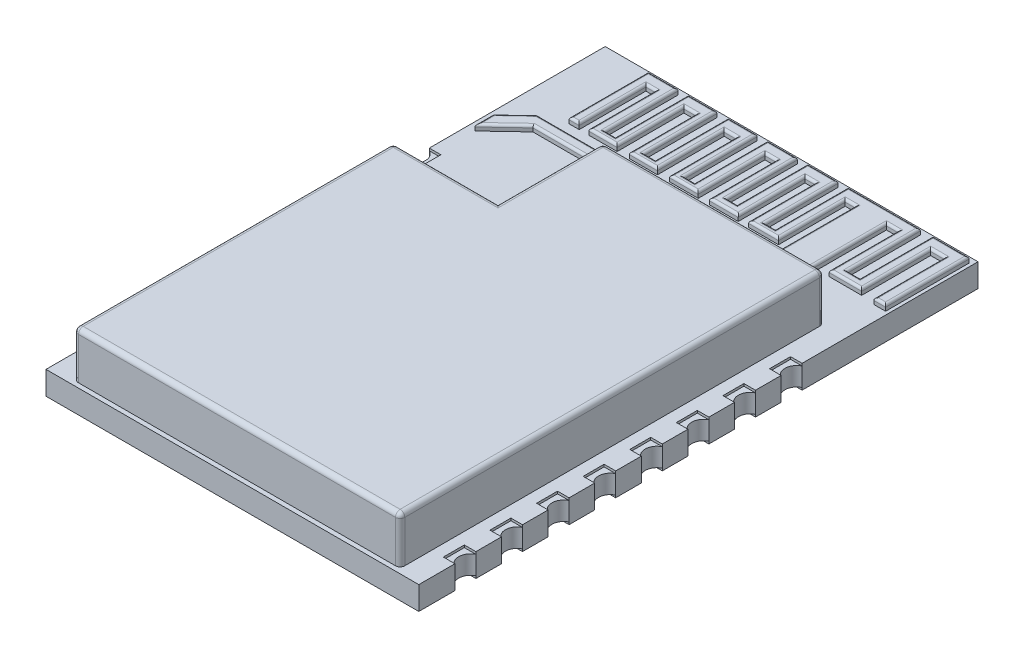
SolidWorks part; units mm, degrees
ref_plane "前基準面" through (0, 0, 0) normal (0, 0, 1) x (1, 0, 0)
ref_plane "上基準面" through (0, 0, 0) normal (0, 1, 0) x (1, 0, 0)
ref_plane "右基準面" through (0, 0, 0) normal (1, 0, 0) x (0, 0, -1)
sketch "草圖1" plane through (0, 0, 0) normal (0, 1, 0) x (1, 0, 0)
  line L5 (-8, 12) -> (8, 12)
  line L6 (-8, 12) -> (-8, -12)
  line L7 (-8, -12) -> (8, -12)
  line L8 (8, 12) -> (8, -12)
  line L9 (-8, 12) -> (8, -12) construction
  line L10 (-8, -12) -> (8, 12) construction
  point P0 (0, 0)
  dimension "D1" = 16
  dimension "24" = 24
extrude "填料-伸長1" add sketch "草圖1" along normal blind 1
sketch "草圖2" plane through (0, 1, 0) normal (0, 1, 0) x (1, 0, 0)
  line L0 (0, 0) -> (0, -5.3119)
  line L1 (-8.003, -9.55) -> (-7.503, -9.55)
  line L2 (-8.003, -9.55) -> (-8.003, -10.45)
  line L3 (-8.003, -10.45) -> (-7.503, -10.45)
  line L4 (-7.503, -9.55) -> (-7.503, -10.45)
  line L5 (8.003, -10.45) -> (7.503, -10.45)
  line L6 (7.503, -9.55) -> (7.503, -10.45)
  line L7 (8.003, -9.55) -> (7.503, -9.55)
  line L8 (8.003, -9.55) -> (8.003, -10.45)
  line L9 (-8.003, -7.55) -> (-8.003, -8.45)
  line L10 (-8.003, -7.55) -> (-7.503, -7.55)
  line L11 (-7.503, -7.55) -> (-7.503, -8.45)
  line L12 (-8.003, -8.45) -> (-7.503, -8.45)
  line L13 (-8.003, -5.55) -> (-8.003, -6.45)
  line L14 (-8.003, -5.55) -> (-7.503, -5.55)
  line L15 (-7.503, -5.55) -> (-7.503, -6.45)
  line L16 (-8.003, -6.45) -> (-7.503, -6.45)
  line L17 (-8.003, -3.55) -> (-8.003, -4.45)
  line L18 (-8.003, -3.55) -> (-7.503, -3.55)
  line L19 (-7.503, -3.55) -> (-7.503, -4.45)
  line L20 (-8.003, -4.45) -> (-7.503, -4.45)
  line L21 (-8.003, -1.55) -> (-8.003, -2.45)
  line L22 (-8.003, -1.55) -> (-7.503, -1.55)
  line L23 (-7.503, -1.55) -> (-7.503, -2.45)
  line L24 (-8.003, -2.45) -> (-7.503, -2.45)
  line L25 (-8.003, 0.45) -> (-8.003, -0.45)
  line L26 (-8.003, 0.45) -> (-7.503, 0.45)
  line L27 (-7.503, 0.45) -> (-7.503, -0.45)
  line L28 (-8.003, -0.45) -> (-7.503, -0.45)
  line L29 (-8.003, 2.45) -> (-8.003, 1.55)
  line L30 (-8.003, 2.45) -> (-7.503, 2.45)
  line L31 (-7.503, 2.45) -> (-7.503, 1.55)
  line L32 (-8.003, 1.55) -> (-7.503, 1.55)
  line L33 (-8.003, 4.45) -> (-8.003, 3.55)
  line L34 (-8.003, 4.45) -> (-7.503, 4.45)
  line L35 (-7.503, 4.45) -> (-7.503, 3.55)
  line L36 (-8.003, 3.55) -> (-7.503, 3.55)
  line L42 (8.003, -8.45) -> (7.503, -8.45)
  line L43 (7.503, -7.55) -> (7.503, -8.45)
  line L44 (8.003, -7.55) -> (7.503, -7.55)
  line L45 (8.003, -7.55) -> (8.003, -8.45)
  line L46 (8.003, -6.45) -> (7.503, -6.45)
  line L47 (7.503, -5.55) -> (7.503, -6.45)
  line L48 (8.003, -5.55) -> (7.503, -5.55)
  line L49 (8.003, -5.55) -> (8.003, -6.45)
  line L50 (8.003, -4.45) -> (7.503, -4.45)
  line L51 (7.503, -3.55) -> (7.503, -4.45)
  line L52 (8.003, -3.55) -> (7.503, -3.55)
  line L53 (8.003, -3.55) -> (8.003, -4.45)
  line L54 (8.003, -2.45) -> (7.503, -2.45)
  line L55 (7.503, -1.55) -> (7.503, -2.45)
  line L56 (8.003, -1.55) -> (7.503, -1.55)
  line L57 (8.003, -1.55) -> (8.003, -2.45)
  line L58 (8.003, -0.45) -> (7.503, -0.45)
  line L59 (7.503, 0.45) -> (7.503, -0.45)
  line L60 (8.003, 0.45) -> (7.503, 0.45)
  line L61 (8.003, 0.45) -> (8.003, -0.45)
  line L62 (8.003, 1.55) -> (7.503, 1.55)
  line L63 (7.503, 2.45) -> (7.503, 1.55)
  line L64 (8.003, 2.45) -> (7.503, 2.45)
  line L65 (8.003, 2.45) -> (8.003, 1.55)
  line L66 (8.003, 3.55) -> (7.503, 3.55)
  line L67 (7.503, 4.45) -> (7.503, 3.55)
  line L68 (8.003, 4.45) -> (7.503, 4.45)
  line L69 (8.003, 4.45) -> (8.003, 3.55)
  point P4 (-8.003, -10)
  line M6 (8, -12) -> (8, 12)
  line M8 (-8, 12) -> (-8, -12)
  dimension "D1" = 2
  dimension "D2" = 8
  dimension "D3" = 8
extrude "除料-伸長1" cut sketch "草圖2" against normal blind 0.1 contours L32 L31 L30 M8 | L28 L27 L26 M8 | L24 L23 L22 M8 | L20 L19 L18 M8 | L16 L15 L14 M8 | L12 L11 L10 M8 | L4 L1 L3 M8 | L7 L6 L5 M6 | L44 L43 L42 M6 | L48 L47 L46 M6 | L52 L51 L50 M6 | L56 L55 L54 M6 | L60 L59 L58 M6 | L68 L67 L66 M6 | L64 L63 L62 M6 | L35 L36 L33 L34
sketch "草圖3" plane through (0, 0, 0) normal (0, -1, 0) x (1, 0, 0)
  line L0 (7, 7.55) -> (7, 8.45)
  line L1 (8, 12) -> (8, -12) construction
  line L6 (7, 9.55) -> (8, 9.55)
  line L7 (7, 9.55) -> (7, 10.45)
  line L8 (7, 10.45) -> (8, 10.45)
  line L9 (8, 9.55) -> (8, 10.45)
  line L10 (-8, 12) -> (8, 12) construction
  line L11 (7, 7.55) -> (8, 7.55)
  line L12 (8, 7.55) -> (8, 8.45)
  line L13 (7, 8.45) -> (8, 8.45)
  line L14 (7, 5.55) -> (7, 6.45)
  line L15 (7, 5.55) -> (8, 5.55)
  line L16 (8, 5.55) -> (8, 6.45)
  line L17 (7, 6.45) -> (8, 6.45)
  line L18 (7, 3.55) -> (7, 4.45)
  line L19 (7, 3.55) -> (8, 3.55)
  line L20 (8, 3.55) -> (8, 4.45)
  line L21 (7, 4.45) -> (8, 4.45)
  line L22 (7, 1.55) -> (7, 2.45)
  line L23 (7, 1.55) -> (8, 1.55)
  line L24 (8, 1.55) -> (8, 2.45)
  line L25 (7, 2.45) -> (8, 2.45)
  line L26 (7, -0.45) -> (7, 0.45)
  line L27 (7, -0.45) -> (8, -0.45)
  line L28 (8, -0.45) -> (8, 0.45)
  line L29 (7, 0.45) -> (8, 0.45)
  line L30 (7, -2.45) -> (7, -1.55)
  line L31 (7, -2.45) -> (8, -2.45)
  line L32 (8, -2.45) -> (8, -1.55)
  line L33 (7, -1.55) -> (8, -1.55)
  line L34 (7, -4.45) -> (7, -3.55)
  line L35 (7, -4.45) -> (8, -4.45)
  line L36 (8, -4.45) -> (8, -3.55)
  line L37 (7, -3.55) -> (8, -3.55)
  line L38 (0, 0) -> (0, -2.1829)
  line L39 (-7, 10.45) -> (-8, 10.45)
  line L40 (-8, 9.55) -> (-8, 10.45)
  line L41 (-7, 9.55) -> (-8, 9.55)
  line L42 (-7, 9.55) -> (-7, 10.45)
  line L43 (-7, -4.45) -> (-8, -4.45)
  line L44 (-8, -4.45) -> (-8, -3.55)
  line L45 (-7, -3.55) -> (-8, -3.55)
  line L46 (-7, -4.45) -> (-7, -3.55)
  line L47 (-7, -2.45) -> (-8, -2.45)
  line L48 (-8, -2.45) -> (-8, -1.55)
  line L49 (-7, -1.55) -> (-8, -1.55)
  line L50 (-7, -2.45) -> (-7, -1.55)
  line L51 (-7, -0.45) -> (-8, -0.45)
  line L52 (-8, -0.45) -> (-8, 0.45)
  line L53 (-7, 0.45) -> (-8, 0.45)
  line L54 (-7, -0.45) -> (-7, 0.45)
  line L55 (-7, 1.55) -> (-8, 1.55)
  line L56 (-8, 1.55) -> (-8, 2.45)
  line L57 (-7, 2.45) -> (-8, 2.45)
  line L58 (-7, 1.55) -> (-7, 2.45)
  line L59 (-7, 3.55) -> (-8, 3.55)
  line L60 (-8, 3.55) -> (-8, 4.45)
  line L61 (-7, 4.45) -> (-8, 4.45)
  line L62 (-7, 3.55) -> (-7, 4.45)
  line L63 (-7, 5.55) -> (-8, 5.55)
  line L64 (-8, 5.55) -> (-8, 6.45)
  line L65 (-7, 6.45) -> (-8, 6.45)
  line L66 (-7, 5.55) -> (-7, 6.45)
  line L67 (-7, 7.55) -> (-8, 7.55)
  line L68 (-8, 7.55) -> (-8, 8.45)
  line L69 (-7, 8.45) -> (-8, 8.45)
  line L70 (-7, 7.55) -> (-7, 8.45)
  point P8 (8, 10)
  dimension "D1" = 2
  dimension "D2" = 0.9
  dimension "D3" = 8
extrude "除料-伸長2" cut sketch "草圖3" against normal blind 0.1 contours L67 L70 L69 L9 | L63 L66 L65 L9 | L59 L62 L61 L9 | L51 L54 L53 L9 | L47 L50 L49 L9 | L43 L46 L45 L9 | L33 L30 L31 L7 | L29 L26 L27 L7 | L25 L22 L23 L7 | L21 L18 L19 L7 | L13 L0 L11 L7 | L8 L7 L6 | L41 L40 L39 L42 | L58 L57 L56 L55 | L36 L37 L34 L35 | L17 L16 L15 L14
sketch "草圖8" plane through (0, 1, 0) normal (0, 1, 0) x (1, 0, 0)
  line L0 (-8, -12) -> (8, -12) construction
  line L1 (-1, 0.6) -> (3.7, 0.6)
  line L2 (-1, 0.6) -> (-1, -4.1)
  line L3 (-1, -4.1) -> (3.7, -4.1)
  line L4 (3.7, 0.6) -> (3.7, -4.1)
  line L5 (-1, 0.6) -> (3.7, -4.1) construction
  line L6 (-1, -4.1) -> (3.7, 0.6) construction
  line L7 (-8, -2.45) -> (-8, -3.55) construction
  point P0 (1.35, -1.75)
  dimension "D1" = 7.9
  dimension "D2" = 7
  dimension "D3" = 4.7
  dimension "D4" = 4.7
extrude "除料-伸長3" cut sketch "草圖8" against normal blind 0.1
sketch "草圖12" plane through (0, 0.9, 0) normal (0, 1, 0) x (1, 0, 0)
  line L0 (-1, 0.6) -> (-1, -4.1) construction
  line L1 (-1, -4.1) -> (3.7, -4.1) construction
  circle A1 centre (-0.51, -3.65) radius 0.2
  circle A2 centre (0.42, -3.65) radius 0.2
  circle A3 centre (1.35, -3.65) radius 0.2
  circle A4 centre (2.28, -3.65) radius 0.2
  circle A5 centre (3.21, -3.65) radius 0.2
  circle A6 centre (-0.51, -2.72) radius 0.2
  circle A7 centre (0.42, -2.72) radius 0.2
  circle A8 centre (1.35, -2.72) radius 0.2
  circle A9 centre (2.28, -2.72) radius 0.2
  circle A10 centre (3.21, -2.72) radius 0.2
  circle A11 centre (-0.51, -1.79) radius 0.2
  circle A12 centre (0.42, -1.79) radius 0.2
  circle A13 centre (1.35, -1.79) radius 0.2
  circle A14 centre (2.28, -1.79) radius 0.2
  circle A15 centre (3.21, -1.79) radius 0.2
  circle A16 centre (-0.51, -0.86) radius 0.2
  circle A17 centre (0.42, -0.86) radius 0.2
  circle A18 centre (1.35, -0.86) radius 0.2
  circle A19 centre (2.28, -0.86) radius 0.2
  circle A20 centre (3.21, -0.86) radius 0.2
  circle A21 centre (-0.51, 0.07) radius 0.2
  circle A22 centre (0.42, 0.07) radius 0.2
  circle A23 centre (1.35, 0.07) radius 0.2
  circle A24 centre (2.28, 0.07) radius 0.2
  circle A25 centre (3.21, 0.07) radius 0.2
  dimension "D1" = 0.49
  dimension "D2" = 0.45
  dimension "D3" = 5
  dimension "D4" = 5
extrude "除料-伸長4" cut sketch "草圖12" against normal blind 0.1
sketch "草圖13" plane through (0, 1, 0) normal (0, 1, 0) x (1, 0, 0)
  line L5 (-1, 0.6) -> (3.7, 0.6)
  line L6 (-1, 0.6) -> (-1, -4.1)
  line L7 (-1, -4.1) -> (3.7, -4.1)
  line L8 (3.7, 0.6) -> (3.7, -4.1)
extrude "填料-伸長2" add sketch "草圖13" against normal blind 0.5
sketch "草圖15" plane through (0, 0, 0) normal (0, -1, 0) x (1, 0, 0)
  line L0 (-8, 12) -> (8, 12) construction
  line L1 (1, -0.6) -> (-3.7, -0.6)
  line L2 (1, -0.6) -> (1, 4.1)
  line L3 (1, 4.1) -> (-3.7, 4.1)
  line L4 (-3.7, -0.6) -> (-3.7, 4.1)
  line L5 (1, -0.6) -> (-3.7, 4.1) construction
  line L6 (1, 4.1) -> (-3.7, -0.6) construction
  line L7 (8, 1.55) -> (8, 0.45) construction
  point P0 (-1.35, 1.75)
  point P9 (8, 1)
  dimension "D1" = 7.9
  dimension "D2" = 7
  dimension "D3" = 4.7
  dimension "D4" = 4.7
extrude "除料-伸長5" cut sketch "草圖15" against normal blind 0.1
sketch "草圖16" plane through (0, 0, 0) normal (0, -1, 0) x (1, 0, 0)
  line L0 (1, 4.1) -> (-3.7, 4.1) construction
  line L1 (1, -0.6) -> (1, 4.1) construction
  circle A0 centre (0.51, 3.61) radius 0.2
  circle A1 centre (-0.42, 3.61) radius 0.2
  circle A2 centre (-1.35, 3.61) radius 0.2
  circle A3 centre (-2.28, 3.61) radius 0.2
  circle A4 centre (-3.21, 3.61) radius 0.2
  circle A5 centre (-3.21, 2.68) radius 0.2
  circle A6 centre (-2.28, 2.68) radius 0.2
  circle A7 centre (-1.35, 2.68) radius 0.2
  circle A8 centre (-0.42, 2.68) radius 0.2
  circle A9 centre (0.51, 2.68) radius 0.2
  circle A10 centre (-3.21, 1.75) radius 0.2
  circle A11 centre (-2.28, 1.75) radius 0.2
  circle A12 centre (-1.35, 1.75) radius 0.2
  circle A13 centre (-0.42, 1.75) radius 0.2
  circle A14 centre (0.51, 1.75) radius 0.2
  circle A15 centre (-3.21, 0.82) radius 0.2
  circle A16 centre (-2.28, 0.82) radius 0.2
  circle A17 centre (-1.35, 0.82) radius 0.2
  circle A18 centre (-0.42, 0.82) radius 0.2
  circle A19 centre (0.51, 0.82) radius 0.2
  circle A20 centre (-3.21, -0.11) radius 0.2
  circle A21 centre (-2.28, -0.11) radius 0.2
  circle A22 centre (-1.35, -0.11) radius 0.2
  circle A23 centre (-0.42, -0.11) radius 0.2
  circle A24 centre (0.51, -0.11) radius 0.2
  dimension "D1" = 0.49
  dimension "D2" = 0.49
  dimension "D3" = 5
  dimension "D4" = 5
extrude "除料-伸長6" cut sketch "草圖16" against normal blind 0.25
sketch "草圖17" plane through (0, 1, 0) normal (0, 1, 0) x (1, 0, 0)
  line L0 (-8, -12) -> (8, -12) construction
  line L5 (-2.5, 6.4) -> (7, 6.4)
  line L6 (-7, 1.4) -> (-7, -10.8)
  line L7 (-7, -10.8) -> (7, -10.8)
  line L8 (7, 6.4) -> (7, -10.8)
  line L9 (-8, 12) -> (-8, 4.45) construction
  line L10 (8, 4.45) -> (8, 12) construction
  line L16 (-2.5, 6.4) -> (-2.5, 1.9)
  line L17 (-2.5, 1.9) -> (-7, 1.9)
  line L18 (-7, 1.9) -> (-7, 1.4)
  dimension "D1" = 1.2
  dimension "D2" = 1
  dimension "D3" = 1
extrude "填料-伸長4" add sketch "草圖17" along normal blind 2
sketch "草圖18" plane through (0, 1, 0) normal (0, 1, 0) x (1, 0, 0)
  line L1 (-8, 4.45) -> (-8, 3.55)
  line L3 (-8, 2.45) -> (-8, 1.55)
  line L4 (-8, 0.45) -> (-8, -0.45)
  line L5 (-8, -1.55) -> (-8, -2.45)
  line L6 (-8, -3.55) -> (-8, -4.45)
  line L7 (-8, -5.55) -> (-8, -6.45)
  line L8 (-8, -7.55) -> (-8, -8.45)
  line L9 (-8, -9.55) -> (-8, -10.45)
  line L12 (8, 4.45) -> (8, 3.55)
  line L13 (8, 2.45) -> (8, 1.55)
  line L14 (8, 0.45) -> (8, -0.45)
  line L15 (8, -1.55) -> (8, -2.45)
  line L16 (8, -3.55) -> (8, -4.45)
  line L17 (8, -5.55) -> (8, -6.45)
  line L18 (8, -7.55) -> (8, -8.45)
  line L19 (8, -9.55) -> (8, -10.45)
  arc A0 (-8, 4.45) -> (-8, 3.55) centre (-8.2179, 4) cw
  arc A1 (-8, 2.45) -> (-8, 1.55) centre (-8.2179, 2) cw
  arc A2 (-8, 0.45) -> (-8, -0.45) centre (-8.2179, 0) cw
  arc A3 (-8, -1.55) -> (-8, -2.45) centre (-8.2179, -2) cw
  arc A4 (-8, -3.55) -> (-8, -4.45) centre (-8.2179, -4) cw
  arc A5 (-8, -5.55) -> (-8, -6.45) centre (-8.2179, -6) cw
  arc A6 (-8, -7.55) -> (-8, -8.45) centre (-8.2179, -8) cw
  arc A7 (-8, -9.55) -> (-8, -10.45) centre (-8.2179, -10) cw
  arc A8 (8, 4.45) -> (8, 3.55) centre (8.2179, 4) ccw
  arc A9 (8, 2.45) -> (8, 1.55) centre (8.2179, 2) ccw
  arc A10 (8, 0.45) -> (8, -0.45) centre (8.2179, 0) ccw
  arc A11 (8, -1.55) -> (8, -2.45) centre (8.2179, -2) ccw
  arc A12 (8, -3.55) -> (8, -4.45) centre (8.2179, -4) ccw
  arc A13 (8, -5.55) -> (8, -6.45) centre (8.2179, -6) ccw
  arc A14 (8, -7.55) -> (8, -8.45) centre (8.2179, -8) ccw
  arc A15 (8, -9.55) -> (8, -10.45) centre (8.2179, -10) ccw
  dimension "D1" = 8
extrude "除料-伸長7" cut sketch "草圖18" against normal blind 2
sketch "草圖19" plane through (0, 1, 0) normal (0, 1, 0) x (1, 0, 0)
  line L0 (-144.5969, 121.1687) -> (-19.9302, 121.1687) construction
  line L1 (-7, -10.8) -> (-7, -11.8025)
  line L2 (-7, -11.8025) -> (7, -11.8025)
  line L3 (7, -10.8) -> (7, -11.8025)
  line L4 (7, -10.8) -> (7, -11.8025)
  line L5 (-7, -10.8) -> (7, -10.8)
extrude "填料-伸長5" add sketch "草圖19" along normal up to surface (2 mm away) contours L5 L1 L2 L3 up to face at (-0.8333, 3, 0.8333)
sketch "草圖20" plane through (0, 1, 0) normal (0, 1, 0) x (1, 0, 0)
  line L0 (23.4441, 125.3473) -> (148.1108, 125.3473) construction
  line L1 (2.7746, 7.2994) -> (2.7746, 6.4)
  line L3 (7, 6.4) -> (-2.5, 6.4) construction
  line L4 (2.7746, 7.2994) -> (4.8557, 7.2994)
  line L5 (4.8557, 7.2994) -> (4.8557, 11.2142)
  line L6 (4.8557, 11.2142) -> (5.3615, 11.2142)
  line L7 (5.3615, 11.2142) -> (5.3615, 8.253)
  line L8 (5.3615, 8.253) -> (6.7537, 8.253)
  line L9 (6.7537, 8.253) -> (6.7537, 11.2142)
  line L10 (6.7537, 11.2142) -> (7.3504, 11.2142)
  line L11 (7.3504, 11.2142) -> (7.3504, 8.1756)
  line L12 (7.3504, 8.1756) -> (7.8586, 8.1756)
  line L13 (7.8586, 8.1756) -> (7.8586, 11.7556)
  line L14 (7.8586, 11.7556) -> (6.3117, 11.7556)
  line L15 (6.3117, 11.7556) -> (6.3117, 8.6286)
  line L16 (6.3117, 8.6286) -> (5.8587, 8.6286)
  line L17 (5.8587, 8.6286) -> (5.7703, 8.6286)
  line L18 (5.7703, 8.6286) -> (5.7703, 11.7556)
  line L19 (5.7703, 11.7556) -> (2.6765, 11.7556)
  line L20 (2.6765, 11.7556) -> (2.6765, 8.6286)
  line L21 (2.6765, 8.6286) -> (2.2345, 8.6286)
  line L22 (2.2345, 8.6286) -> (2.2345, 11.7556)
  line L23 (2.2345, 11.7556) -> (0.9417, 11.7556)
  line L24 (0.9417, 11.7556) -> (0.9417, 8.7281)
  line L25 (0.9417, 8.7281) -> (0.4887, 8.7281)
  line L26 (0.4887, 8.7281) -> (0.4887, 11.7556)
  line L27 (0.4887, 11.7556) -> (-0.782, 11.7556)
  line L28 (-0.782, 11.7556) -> (-0.782, 8.6286)
  line L29 (-0.782, 8.6286) -> (-1.235, 8.6286)
  line L30 (-1.235, 8.6286) -> (-1.235, 11.7556)
  line L31 (-1.235, 11.7556) -> (-2.4725, 11.7556)
  line L32 (-2.4725, 11.7556) -> (-2.4725, 8.6286)
  line L33 (-2.4725, 8.6286) -> (-2.9587, 8.6286)
  line L34 (-2.9587, 8.6286) -> (-2.9587, 11.7556)
  line L35 (-2.9587, 11.7556) -> (-4.1852, 11.7556)
  line L36 (-4.1852, 11.7556) -> (-4.1852, 8.6286)
  line L37 (-4.1852, 8.6286) -> (-4.6323, 8.6286)
  line L38 (-4.6323, 8.6286) -> (-4.6323, 11.7556)
  line L39 (-4.6323, 11.7556) -> (-5.9045, 11.7556)
  line L40 (-5.9045, 11.7556) -> (-5.9045, 8.3512)
  line L41 (-5.9045, 8.3512) -> (-5.4695, 8.3512)
  line L42 (-5.4695, 8.3512) -> (-5.4695, 11.2142)
  line L43 (-5.4695, 11.2142) -> (-5.0563, 11.2142)
  line L44 (-5.0563, 11.2142) -> (-5.0563, 8.3512)
  line L45 (-5.0563, 8.3512) -> (-3.8385, 8.3512)
  line L46 (-3.8385, 8.3512) -> (-3.8385, 11.2142)
  line L47 (-3.8385, 11.2142) -> (-3.3166, 11.2142)
  line L48 (-3.3166, 11.2142) -> (-3.3166, 8.3512)
  line L49 (-3.3166, 8.3512) -> (-2.1096, 8.3512)
  line L50 (-2.1096, 8.3512) -> (-2.1096, 11.2142)
  line L51 (-2.1096, 11.2142) -> (-1.5877, 11.2142)
  line L52 (-1.5877, 11.2142) -> (-1.5877, 8.3512)
  line L53 (-1.5877, 8.3512) -> (-0.3589, 8.3512)
  line L54 (-0.3589, 8.3512) -> (-0.3589, 11.2142)
  line L55 (-0.3589, 11.2142) -> (0.1195, 11.2142)
  line L56 (0.1195, 11.2142) -> (0.1195, 8.3512)
  line L57 (0.1195, 8.3512) -> (1.3591, 8.3512)
  line L58 (1.3591, 8.3512) -> (1.3591, 11.2142)
  line L59 (1.3591, 11.2142) -> (1.8049, 11.2142)
  line L60 (1.8049, 11.2142) -> (1.8049, 8.3512)
  line L61 (1.8049, 8.3512) -> (3.088, 8.3512)
  line L62 (3.088, 8.3512) -> (3.088, 11.2142)
  line L63 (3.088, 11.2142) -> (3.523, 11.2142)
  line L64 (3.523, 11.2142) -> (3.523, 7.764)
  line L65 (3.523, 7.764) -> (-6.6874, 7.764)
  line L66 (-6.6874, 7.764) -> (-7.6552, 6.8497)
  line L67 (-7.6552, 6.8497) -> (-7.6552, 6.1428)
  line L68 (-6.3743, 7.2733) -> (2.2333, 7.2733)
  line L69 (2.2333, 7.2733) -> (2.25, 6.4)
  line L70 (-6.3743, 7.2733) -> (-7.5709, 6.1428)
  line L71 (7, 6.4) -> (-2.5, 6.4) construction
  line L72 (2.25, 6.4) -> (2.7746, 6.4)
  line L73 (-7.6552, 6.1428) -> (-7.6552, 6.0749)
  line L75 (-7.5709, 6.1428) -> (-7.6552, 6.0632)
  line L76 (-7.6552, 6.0632) -> (-7.6552, 6.0749)
ref_plane "平面1" through (8, 1, -4.45) normal (0, 0, -1) x (-1, 0, 0)
extrude "填料-伸長7" add sketch "草圖20" along normal blind 0.25 contours L65 L66 L67 L73 L76 L75 L70 L68 L69 L72 L1 L4 L5 L6 L7 L8 L9 L10 L11 L12 L13 L14 L15 L16 L17 L18 L19 L20 L21 L22 L23 L24 L25 L26 L27 L28 L29 L30 L31 L32 L33 L34 L35 L36 L37 L38 L39 L40 L41 L42 L43 L44 L45 L46 L47 L48 L49 L50 L51 L52 L53 L54 L55 L56 L57 L58 L59 L60 L61 L62 L63 L64
fillet "圓角1" radius 0.2 11 edges at (0, 3, 11.8025) (-7, 3, 4.9512) (-4.75, 3, -1.9) (-2.5, 3, -4.15) (2.25, 3, -6.4) (7, 3, 2.7012) (7, 2, 11.8025) (-7, 2, 11.8025) (-7, 2, -1.9) (7, 2, -6.4) (-2.5, 2, -6.4)
fillet "圓角2" radius 0.1 70 edges at (2.7746, 1.125, -6.4) (2.25, 1.125, -6.4) (3.3055, 1.25, -11.2142) (3.088, 1.25, -9.7827) (2.4465, 1.25, -8.3512) (1.8049, 1.25, -9.7827) (1.582, 1.25, -11.2142) (1.3591, 1.25, -9.7827) (0.7393, 1.25, -8.3512) (0.1195, 1.25, -9.7827) (-0.1197, 1.25, -11.2142) (-0.3589, 1.25, -9.7827) (-0.9733, 1.25, -8.3512) (-1.5877, 1.25, -9.7827) (-1.8486, 1.25, -11.2142) (-2.1096, 1.25, -9.7827) (-2.7131, 1.25, -8.3512) (-3.3166, 1.25, -9.7827) (-3.5775, 1.25, -11.2142) (-3.8385, 1.25, -9.7827) (-4.4474, 1.25, -8.3512) (-5.0563, 1.25, -9.7827) (-5.2629, 1.25, -11.2142) (-5.4695, 1.25, -9.7827) (-5.687, 1.25, -8.3512) (-5.9045, 1.25, -10.0534) (-5.2684, 1.25, -11.7556) (-4.6323, 1.25, -10.1921) (-4.4087, 1.25, -8.6286) (-4.1852, 1.25, -10.1921) (-3.572, 1.25, -11.7556) (-2.9587, 1.25, -10.1921) (-2.7156, 1.25, -8.6286) (-2.4725, 1.25, -10.1921) (-1.8538, 1.25, -11.7556) (-1.235, 1.25, -10.1921) (-1.0085, 1.25, -8.6286) (-0.782, 1.25, -10.1921) (-0.1466, 1.25, -11.7556) (0.4887, 1.25, -10.2418) (0.7152, 1.25, -8.7281) (0.9417, 1.25, -10.2418) (1.5881, 1.25, -11.7556) (2.2345, 1.25, -10.1921) (2.4555, 1.25, -8.6286) (2.6765, 1.25, -10.1921) (4.2234, 1.25, -11.7556) (5.7703, 1.25, -10.1921) (6.041, 1.25, -8.6286) (6.3117, 1.25, -10.1921) (7.0852, 1.25, -11.7556) (7.8586, 1.25, -9.9656) (7.6045, 1.25, -8.1756) (7.3504, 1.25, -9.6949) (7.052, 1.25, -11.2142) (6.7537, 1.25, -9.7336) (6.0576, 1.25, -8.253) (5.3615, 1.25, -9.7336) (5.1086, 1.25, -11.2142) (4.8557, 1.25, -9.2568) (3.8151, 1.25, -7.2994) (2.7746, 1.25, -6.8497) (2.5123, 1.25, -6.4) (2.2417, 1.25, -6.8367) (-2.0705, 1.25, -7.2733) (-7.0147, 1.25, -6.6683) (-7.6552, 1.25, -6.4565) (-7.1713, 1.25, -7.3069) (-1.5822, 1.25, -7.764) (3.523, 1.25, -9.4891)
